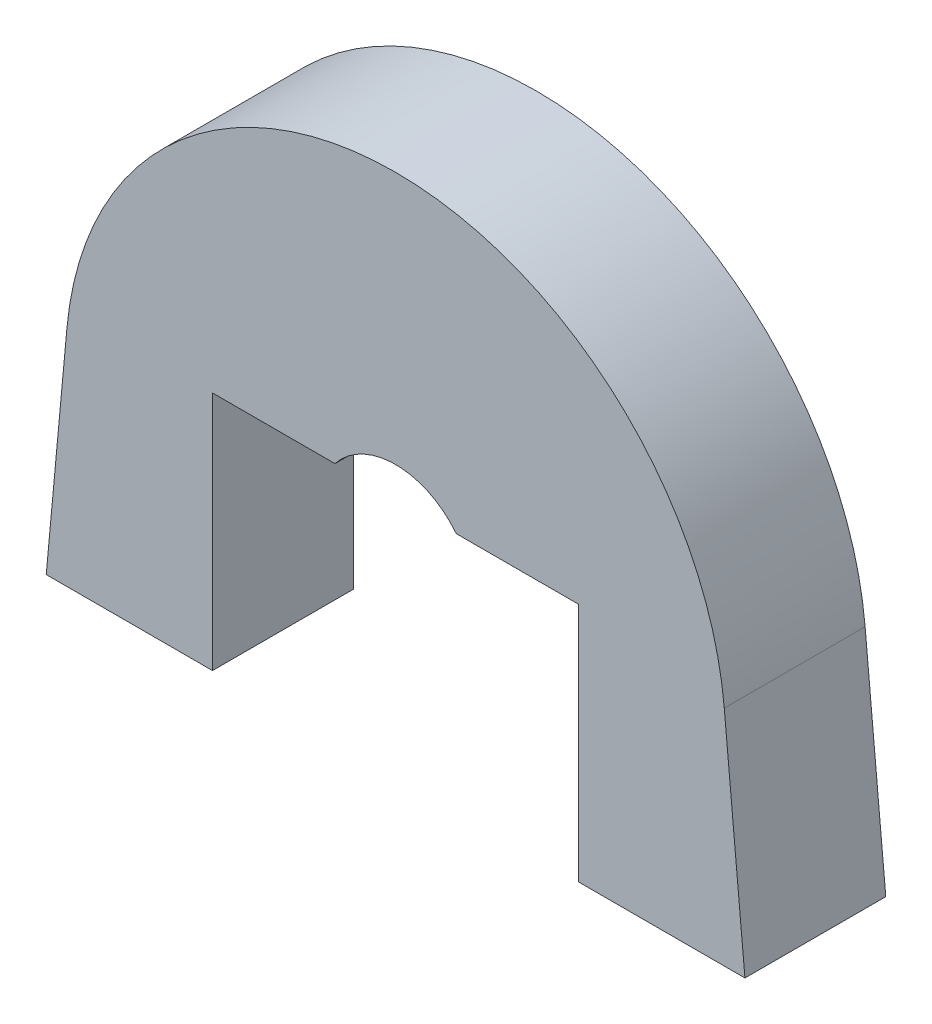
SolidWorks part; units mm, degrees
material "ABS"
ref_plane "Front Plane" through (0, 0, 0) normal (0, 0, 1) x (1, 0, 0)
ref_plane "Top Plane" through (0, 0, 0) normal (0, 1, 0) x (1, 0, 0)
ref_plane "Right Plane" through (0, 0, 0) normal (1, 0, 0) x (0, 0, -1)
sketch "Croquis1" plane through (0, 0, 0) normal (0, 0, 1) x (1, 0, 0)
  line L4 (15.875, -8.77) -> (8.32, -8.77)
  line L5 (8.32, -8.77) -> (8.32, 2.1573)
  line L6 (8.32, 2.1573) -> (2.7561, 2.1573)
  line L9 (0, -55) -> (0, 55) construction
  line L18 (-15.875, -8.77) -> (-14.9363, 1.3812)
  line L19 (15.875, -8.77) -> (14.9363, 1.3812)
  line L20 (-15.875, -8.77) -> (-8.32, -8.77)
  line L21 (-8.32, -8.77) -> (-8.32, 2.1573)
  line L22 (-8.32, 2.1573) -> (-2.7561, 2.1573)
  arc A0 (14.9363, 1.3812) -> (-14.9363, 1.3812) centre (0, 0) ccw
  arc A1 (2.7561, 2.1573) -> (-2.7561, 2.1573) centre (0, 0) ccw
  dimension "D1" = 7
  dimension "D2" = 30
  dimension "D3" = 2.1573
  dimension "D4" = 10.9273
  dimension "D5" = 8.32
  dimension "D8" = 7.555
extrude "Saliente-Extruir1" add sketch "Croquis1" along normal mid plane 6.4
sketch "Croquis2" plane through (0, -8.77, 0) normal (0, -1, 0) x (1, 0, 0)
  line L0 (0, -3.52) -> (0, 3.52) construction
  circle A0 centre (-12.7, 0) radius 1.5
  circle A2 centre (12.7, 0) radius 1.5
  point P4 (0, 0)
  point P6 (0, 0)
  dimension "D2" = 3
  dimension "D1" = 25.4
extrude "Cortar-Extruir1" cut sketch "Croquis2" against normal blind 5
